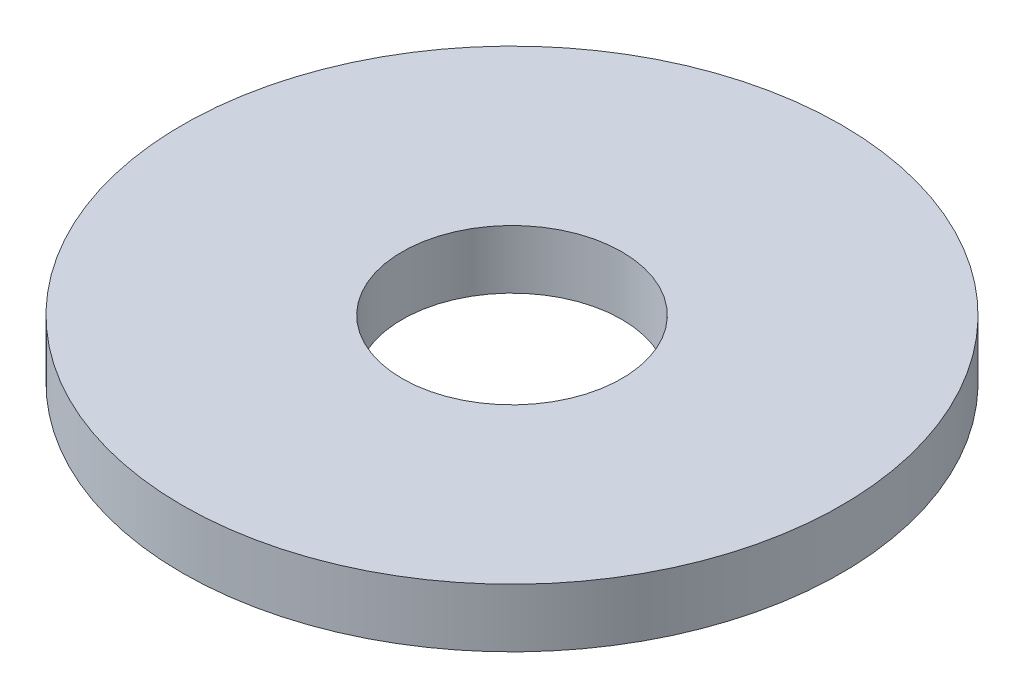
SolidWorks part; units mm, degrees
material "Stainless Steel (ferritic)"
ref_plane "Front Plane" through (0, 0, 0) normal (0, 0, 1) x (1, 0, 0)
ref_plane "Top Plane" through (0, 0, 0) normal (0, 1, 0) x (1, 0, 0)
ref_plane "Right Plane" through (0, 0, 0) normal (1, 0, 0) x (0, 0, -1)
sketch "Sketch1" plane through (0, 0, 0) normal (0, 1, 0) x (1, 0, 0)
  circle A0 centre (0, 0) radius 3
  circle A1 centre (0, 0) radius 9
  dimension "D1" = 18
  dimension "D2" = 6
extrude "Boss-Extrude1" add sketch "Sketch1" along normal blind 1.6
